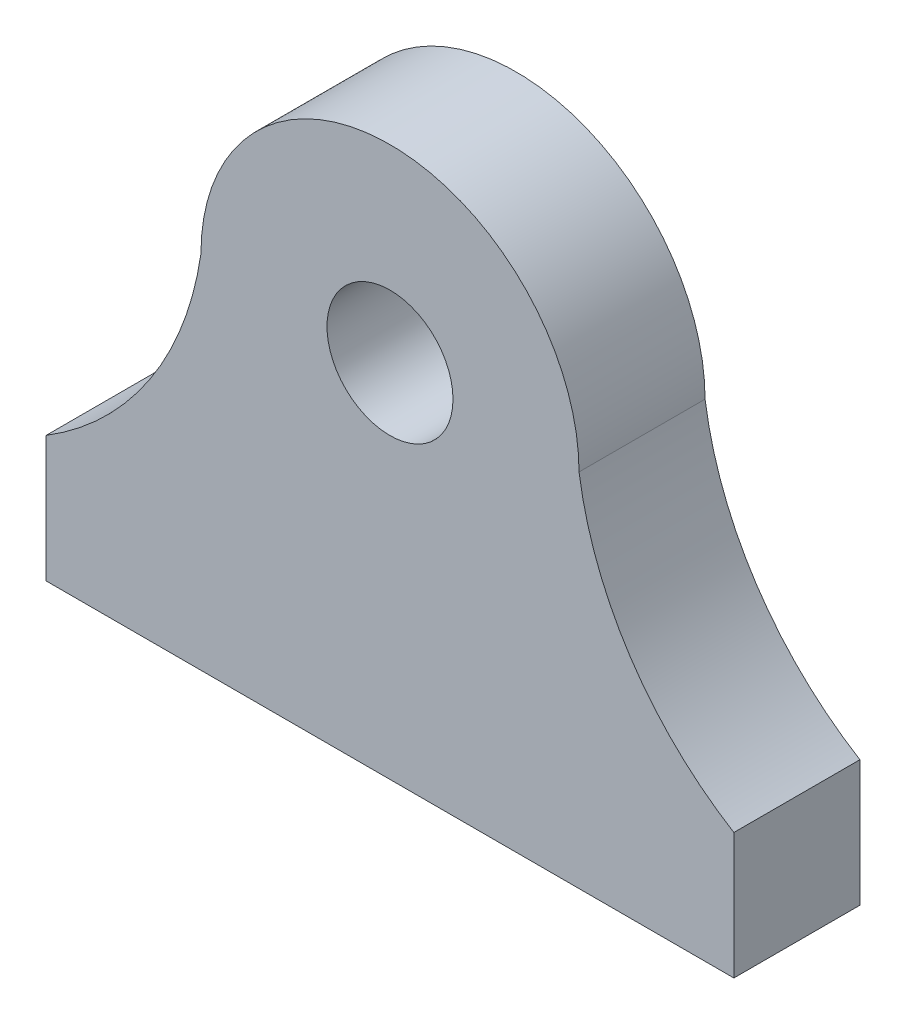
SolidWorks part; units mm, degrees
ref_plane "Plano frontal" through (0, 0, 0) normal (0, 0, 1) x (1, 0, 0)
ref_plane "Plano superior" through (0, 0, 0) normal (0, 1, 0) x (1, 0, 0)
ref_plane "Plano direito" through (0, 0, 0) normal (1, 0, 0) x (0, 0, -1)
sketch "Esboço1" plane through (0, 0, 0) normal (0, 0, 1) x (1, 0, 0)
  line L6 (0, 5) -> (0, -5) construction
  line L14 (-27.2861, -18.6299) -> (-27.2861, -28.6299)
  line L15 (-27.2861, -28.6299) -> (27.2861, -28.6299)
  line L16 (27.2861, -18.6299) -> (27.2861, -28.6299)
  circle A2 centre (0, 0) radius 5
  arc A3 (15, 0) -> (-15, 0) centre (0, 0) ccw
  arc A4 (-15, 0) -> (-27.2861, -18.6299) centre (-41.0271, 3.7983) cw
  arc A5 (15, 0) -> (27.2861, -18.6299) centre (41.0271, 3.7983) ccw
  point P8 (0, -18.6299)
  dimension "D1" = 10
extrude "Ressalto-extrusão1" add sketch "Esboço1" along normal blind 10
